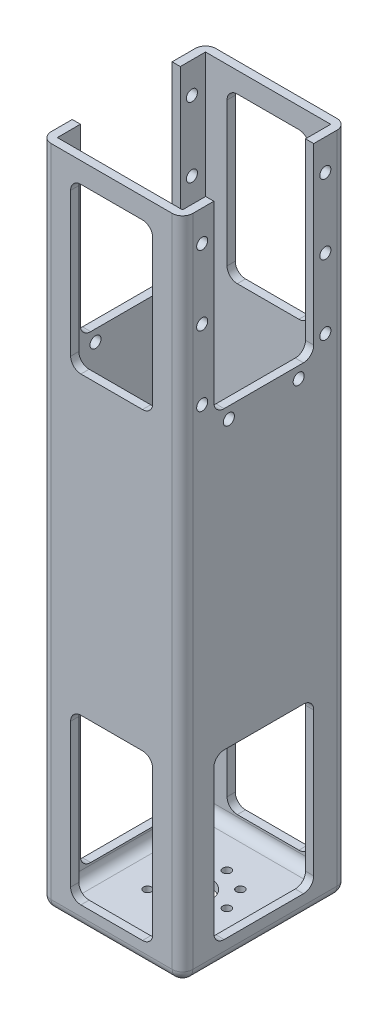
SolidWorks part; units mm, degrees
material "PLA"
ref_plane "Front Plane" through (0, 0, 0) normal (0, 0, 1) x (1, 0, 0)
ref_plane "Top Plane" through (0, 0, 0) normal (0, 1, 0) x (1, 0, 0)
ref_plane "Right Plane" through (0, 0, 0) normal (1, 0, 0) x (0, 0, -1)
other "Center of Mass"
sketch "Sketch1" plane through (0, 0, 0) normal (0, 1, 0) x (1, 0, 0)
  circle A0 centre (0, 0) radius 8 construction
  circle A1 centre (0, 8) radius 1
  circle A2 centre (5.6569, 5.6569) radius 1
  circle A3 centre (8, 0) radius 1
  circle A4 centre (5.6569, -5.6569) radius 1
  circle A5 centre (0, -8) radius 1
  circle A6 centre (-5.6569, -5.6569) radius 1
  circle A7 centre (-8, 0) radius 1
  circle A8 centre (-5.6569, 5.6569) radius 1
  circle A9 centre (0, 0) radius 4.25
  point P21 (0, 0)
  dimension "D1" = 16
  dimension "D2" = 2
  dimension "D4" = 8.5
  dimension "D3" = 8
sketch "Sketch2" plane through (0, 0, 0) normal (0, 1, 0) x (1, 0, 0)
  line L1 (-17.25, -20.05) -> (17.25, -20.05)
  line L2 (-17.25, -20.05) -> (-17.25, 20.05)
  line L3 (-17.25, 20.05) -> (17.25, 20.05)
  line L4 (17.25, -20.05) -> (17.25, 20.05)
  line L5 (-17.25, -20.05) -> (17.25, 20.05) construction
  line L6 (-17.25, 20.05) -> (17.25, -20.05) construction
  point P0 (0, 0)
  dimension "D1" = 34.5
  dimension "D2" = 40.1
extrude "Boss-Extrude1" add sketch "Sketch2" along normal blind 2
extrude "Cut-Extrude2" cut sketch "Sketch1" along normal through all
sketch "Sketch3" plane through (0, 2, 0) normal (0, 1, 0) x (1, 0, 0)
  line L5 (-17.25, -20.05) -> (17.25, -20.05) construction
  line L10 (17.25, -20.05) -> (17.25, 20.05) construction
  line L11 (17.25, 20.05) -> (-17.25, 20.05) construction
  line L12 (-17.25, 20.05) -> (-17.25, -20.05) construction
  line L13 (-17.25, -20.05) -> (17.25, -20.05)
  line L14 (17.25, -20.05) -> (17.25, 20.05)
  line L15 (17.25, 20.05) -> (-17.25, 20.05)
  line L16 (-17.25, 20.05) -> (-17.25, -20.05)
  line L17 (15.25, 18.05) -> (-15.25, 18.05)
  line L18 (-15.25, 18.05) -> (-15.25, -18.05)
  line L19 (-15.25, -18.05) -> (15.25, -18.05)
  line L20 (15.25, -18.05) -> (15.25, 18.05)
  dimension "D1" = 2
extrude "Boss-Extrude3" add sketch "Sketch3" along normal blind 160
sketch "Sketch4" plane through (-17.25, 0, 0) normal (-1, 0, 0) x (0, 0, 1)
  line L0 (-11.9182, 120) -> (-11.9182, 159)
  line L1 (-11.9182, 117) -> (-11.9182, 162)
  line L2 (12.4182, 159) -> (12.4182, 120)
  line L3 (12.4182, 162) -> (12.4182, 117)
  line L4 (-11.9182, 117) -> (12.4182, 117)
  line L6 (-11.9182, 162) -> (12.4182, 162)
  line L7 (-20.05, 162) -> (20.05, 162) construction
  line L8 (-20.05, 81) -> (20.05, 81) construction
  line L9 (-20.05, 162) -> (-20.05, 0) construction
  line L10 (20.05, 162) -> (20.05, 0) construction
  line L11 (-11.9182, 45) -> (12.4182, 45)
  line L12 (12.4182, 5) -> (12.4182, 45)
  line L13 (-11.9182, 45) -> (-11.9182, 5)
  line L14 (-11.9182, 5) -> (12.4182, 5)
  dimension "D1" = 45
  dimension "D2" = 40
extrude "Cut-Extrude3" cut sketch "Sketch4" against normal through all
sketch "Sketch5" plane through (0, 0, 20.05) normal (0, 0, 1) x (1, 0, 0)
  line L0 (0, 117) -> (0, 45) construction
  line L1 (-10, 5) -> (10, 5)
  line L2 (-10, 5) -> (-10, 45)
  line L3 (-10, 45) -> (10, 45)
  line L4 (10, 5) -> (10, 45)
  line L5 (-10, 5) -> (10, 45) construction
  line L6 (-10, 45) -> (10, 5) construction
  line L7 (-10, 117) -> (10, 117)
  line L8 (-10, 117) -> (-10, 157)
  line L9 (-10, 157) -> (10, 157)
  line L10 (10, 117) -> (10, 157)
  line L11 (-10, 117) -> (10, 157) construction
  line L12 (-10, 157) -> (10, 117) construction
  line L13 (0, 137) -> (0, 162) construction
  line L14 (-17.25, 162) -> (17.25, 162) construction
  line L15 (0, 0) -> (0, 25) construction
  line L16 (-17.25, 0) -> (17.25, 0) construction
  point P0 (0, 25)
  point P5 (0, 137)
  dimension "D1" = 25
  dimension "D2" = 25
  dimension "D3" = 40
  dimension "D4" = 20
extrude "Cut-Extrude4" cut sketch "Sketch5" against normal through all
fillet "Fillet1" radius 2.5 40 edges at (17.25, 81, 20.05) (-17.25, 81, -20.05) (0, 0, -20.05) (17.25, 81, -20.05) (17.25, 0, 0) (0, 0, 20.05) (-17.25, 81, 20.05) (-17.25, 0, 0) (0, 2, 18.05) (-15.25, 2, 0) (0, 2, -18.05) (15.25, 2, 0) (-10, 45, 19.05) (-10, 45, -19.05) (-10, 157, -19.05) (-10, 157, 19.05) (10, 157, 19.05) (10, 157, -19.05) (10, 45, -19.05) (10, 45, 19.05) (-10, 117, 19.05) (10, 117, 19.05) (10, 117, -19.05) (-10, 117, -19.05) (-10, 5, -19.05) (10, 5, -19.05) (-10, 5, 19.05) (10, 5, 19.05) (-16.25, 117, 12.4182) (-16.25, 117, -11.9182) (16.25, 117, -11.9182) (16.25, 117, 12.4182) (16.25, 45, -11.9182) (-16.25, 45, -11.9182) (16.25, 45, 12.4182) (-16.25, 45, 12.4182) (-16.25, 5, 12.4182) (16.25, 5, 12.4182) (16.25, 5, -11.9182) (-16.25, 5, -11.9182)
sketch "Sketch7" plane through (-17.25, 0, 0) normal (-1, 0, 0) x (0, 0, 1)
  line L0 (-17.55, 162) -> (-11.9182, 162) construction
  line L1 (-14.75, 154.5) -> (-14.75, 120.5) construction
  line L2 (15.25, 154.5) -> (15.25, 162) construction
  line L3 (-11.9182, 162) -> (-11.9182, 119.5) construction
  line L4 (-14.75, 120.5) -> (-14.75, 114.2) construction
  line L5 (-14.75, 114.2) -> (15.25, 114.2) construction
  line L6 (15.25, 114.2) -> (15.25, 154.5) construction
  line L10 (12.4182, 162) -> (17.55, 162) construction
  circle A0 centre (-14.75, 154.5) radius 1.35
  circle A1 centre (-14.75, 137.5) radius 1.35
  circle A2 centre (-14.75, 120.5) radius 1.35
  circle A3 centre (15.25, 154.5) radius 1.35
  circle A4 centre (15.25, 137.5) radius 1.35
  circle A5 centre (15.25, 120.5) radius 1.35
  circle A6 centre (-8.25, 114.2) radius 1.35
  circle A7 centre (8.75, 114.2) radius 1.35
  dimension "D1" = 2.7
  dimension "D2" = 2.7
  dimension "D3" = 2.7
  dimension "D4" = 2.7
  dimension "D5" = 2.7
  dimension "D6" = 2.7
  dimension "D7" = 2.7
  dimension "D8" = 2.7
  dimension "D15" = 17
  dimension "D16" = 6.5
  dimension "D17" = 6.5
  dimension "D18" = 6.3
  dimension "D19" = 17
  dimension "D20" = 17
  dimension "D9" = 7.5
  dimension "D10" = 17
  dimension "D11" = 2.8318
  dimension "D12" = 17
  dimension "D13" = 6.3
  dimension "D14" = 30
extrude "Cut-Extrude5" cut sketch "Sketch7" against normal through all
